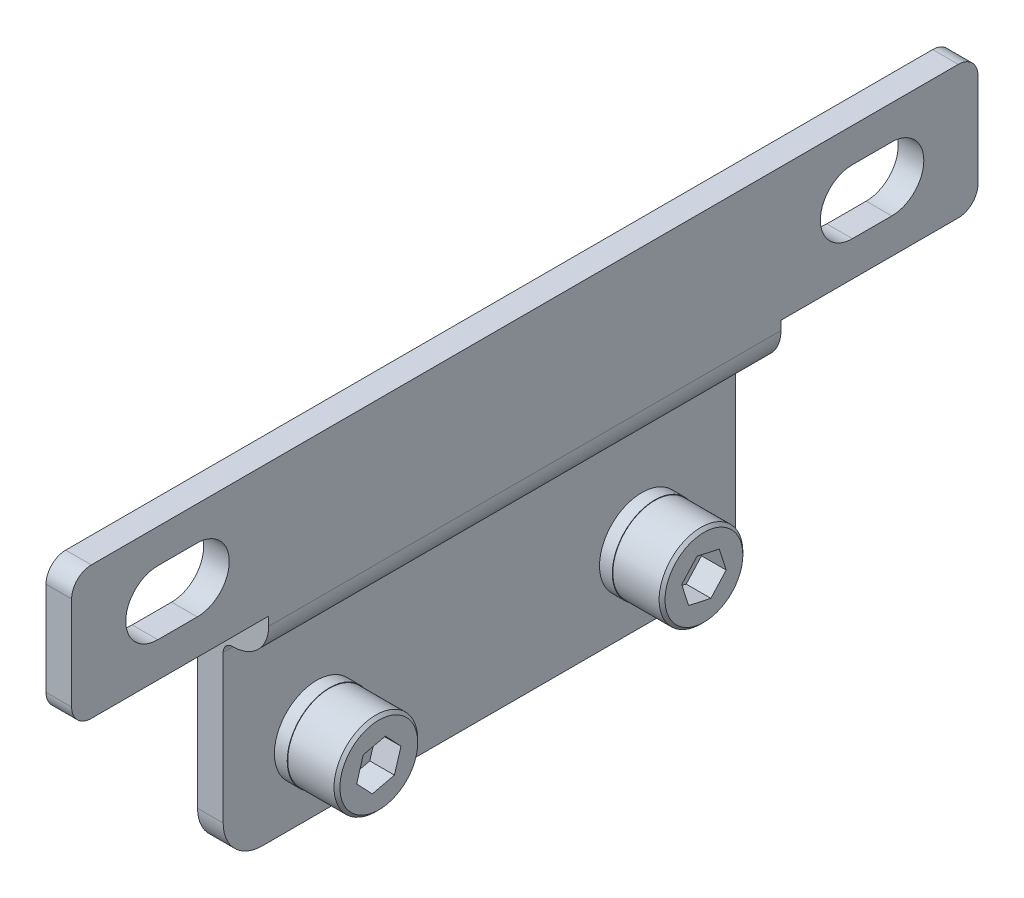
SolidWorks part; units mm, degrees
ref_plane "Front Plane" through (0, 0, 0) normal (0, 0, 1) x (1, 0, 0)
ref_plane "Top Plane" through (0, 0, 0) normal (0, 1, 0) x (1, 0, 0)
ref_plane "Right Plane" through (0, 0, 0) normal (1, 0, 0) x (0, 0, -1)
sketch "Sketch1" plane through (0, 0, 0) normal (0, 0, 1) x (1, 0, 0)
  line L0 (0, 0) -> (2.6, 0)
  line L1 (2.6, 0) -> (2.6, 19)
  line L2 (3.6, 20) -> (3.618, 20)
  line L3 (7.218, 23.6) -> (7.218, 38)
  line L4 (7.218, 38) -> (4.618, 38)
  line L5 (4.618, 38) -> (4.618, 23.6)
  line L6 (3.618, 22.6) -> (3.6, 22.6)
  line L7 (0, 19) -> (0, 0)
  arc A0 (4.618, 23.6) -> (3.618, 22.6) centre (3.618, 23.6) cw
  arc A1 (2.6, 19) -> (3.6, 20) centre (3.6, 19) cw
  arc A2 (3.618, 20) -> (7.218, 23.6) centre (3.618, 23.6) ccw
  arc A3 (3.6, 22.6) -> (0, 19) centre (3.6, 19) ccw
  point P15 (7.218, 20)
  point P18 (0, 22.6)
  dimension "D5" = 1
  dimension "D6" = 3.6
  dimension "D1" = 2.6
  dimension "D2" = 20
  dimension "D3" = 22.6
  dimension "D4" = 18
extrude "Boss-Extrude1" add sketch "Sketch1" along normal mid plane 92
sketch "Sketch2" plane through (7.218, 0, 0) normal (1, 0, 0) x (0, 0, -1)
  line L0 (-46, 0) -> (46, 0) construction
  line L1 (-46, 24.5) -> (-26, 24.5)
  line L2 (-46, 24.5) -> (-46, 0)
  line L3 (-46, 0) -> (-26, 0)
  line L4 (-26, 24.5) -> (-26, 0)
  line L5 (-46, 23.6) -> (-46, 38) construction
  line L6 (46, 24.5) -> (26, 24.5)
  line L7 (46, 24.5) -> (46, 0)
  line L8 (46, 0) -> (26, 0)
  line L9 (26, 24.5) -> (26, 0)
  line L10 (46, 23.6) -> (46, 38) construction
  dimension "D1" = 20
  dimension "D2" = 20
  dimension "D3" = 24.5
extrude "Cut-Extrude1" cut sketch "Sketch2" against normal up to next
fillet "Fillet1" radius 2 4 edges at (5.918, 24.5, -46) (5.918, 38, -46) (5.918, 24.5, 46) (5.918, 38, 46)
fillet "Fillet2" radius 4 2 edges at (1.3, 0, 26) (1.3, 0, -26)
sketch "Sketch3" plane through (7.218, 0, 0) normal (1, 0, 0) x (0, 0, -1)
  line L0 (-37.25, 31.3) -> (-33.25, 31.3) construction
  line L1 (-37.25, 34.55) -> (-33.25, 34.55)
  line L2 (-37.25, 28.05) -> (-33.25, 28.05)
  line L3 (0, 0) -> (0, -5.906) construction
  line L4 (-44, 24.5) -> (-26, 24.5) construction
  line L5 (-46, 26.5) -> (-46, 36) construction
  line L6 (37.25, 31.3) -> (33.25, 31.3) construction
  line L7 (37.25, 34.55) -> (33.25, 34.55)
  line L8 (37.25, 28.05) -> (33.25, 28.05)
  arc A0 (-37.25, 34.55) -> (-37.25, 28.05) centre (-37.25, 31.3) ccw
  arc A1 (-33.25, 28.05) -> (-33.25, 34.55) centre (-33.25, 31.3) ccw
  arc A2 (37.25, 34.55) -> (37.25, 28.05) centre (37.25, 31.3) cw
  arc A3 (33.25, 28.05) -> (33.25, 34.55) centre (33.25, 31.3) cw
  point P2 (-35.25, 31.3)
  point P16 (35.25, 31.3)
  dimension "D1" = 4
  dimension "D2" = 6.5
  dimension "D3" = 6.8
  dimension "D4" = 10.75
extrude "Cut-Extrude2" cut sketch "Sketch3" against normal up to next
sketch "Sketch4" plane through (2.6, 0, 0) normal (1, 0, 0) x (0, 0, -1)
  line L0 (-22, 0) -> (22, 0) construction
  line L1 (-26, 4) -> (-26, 19) construction
  line L2 (26, 19) -> (26, 4) construction
  circle A0 centre (-16.5, 7.5) radius 4.3
  circle A1 centre (16.5, 7.5) radius 4.3
  dimension "D1" = 8.6
  dimension "D4" = 9.5
  dimension "D2" = 7.5
  dimension "D3" = 9.5
extrude "Boss-Extrude2" add sketch "Sketch4" along normal blind 1.3
sketch "Sketch5" plane through (3.9, 0, 0) normal (1, 0, 0) x (0, 0, -1)
  circle A0 centre (-16.5, 7.5) radius 4.25
  circle A1 centre (16.5, 7.5) radius 4.25
  dimension "D1" = 8.5
extrude "Boss-Extrude3" add sketch "Sketch5" along normal blind 5
chamfer "Chamfer1" distance 0.3 angle 45 2 edges at (8.9, 7.5, -20.75) (8.9, 7.5, 12.25)
sketch "Sketch6" plane through (8.9, 0, 0) normal (1, 0, 0) x (0, 0, -1)
  line L1 (-14.9163, 5.8192) -> (-14.2525, 8.0311)
  line L2 (-14.2525, 8.0311) -> (-15.8362, 9.7119)
  line L3 (-15.8362, 9.7119) -> (-18.0837, 9.1808)
  line L4 (-18.0837, 9.1808) -> (-18.7475, 6.9689)
  line L5 (-18.7475, 6.9689) -> (-17.1638, 5.2881)
  line L6 (-17.1638, 5.2881) -> (-14.9163, 5.8192)
  line L7 (14.9464, 5.7913) -> (17.2029, 5.3002)
  line L8 (17.2029, 5.3002) -> (18.7566, 7.0089)
  line L9 (18.7566, 7.0089) -> (18.0536, 9.2087)
  line L10 (18.0536, 9.2087) -> (15.7971, 9.6998)
  line L11 (15.7971, 9.6998) -> (14.2434, 7.9911)
  line L12 (14.2434, 7.9911) -> (14.9464, 5.7913)
  circle A0 centre (-16.5, 7.5) radius 2 construction
  circle A1 centre (16.5, 7.5) radius 2 construction
  dimension "D1" = 4
extrude "Cut-Extrude3" cut sketch "Sketch6" against normal blind 2.5
